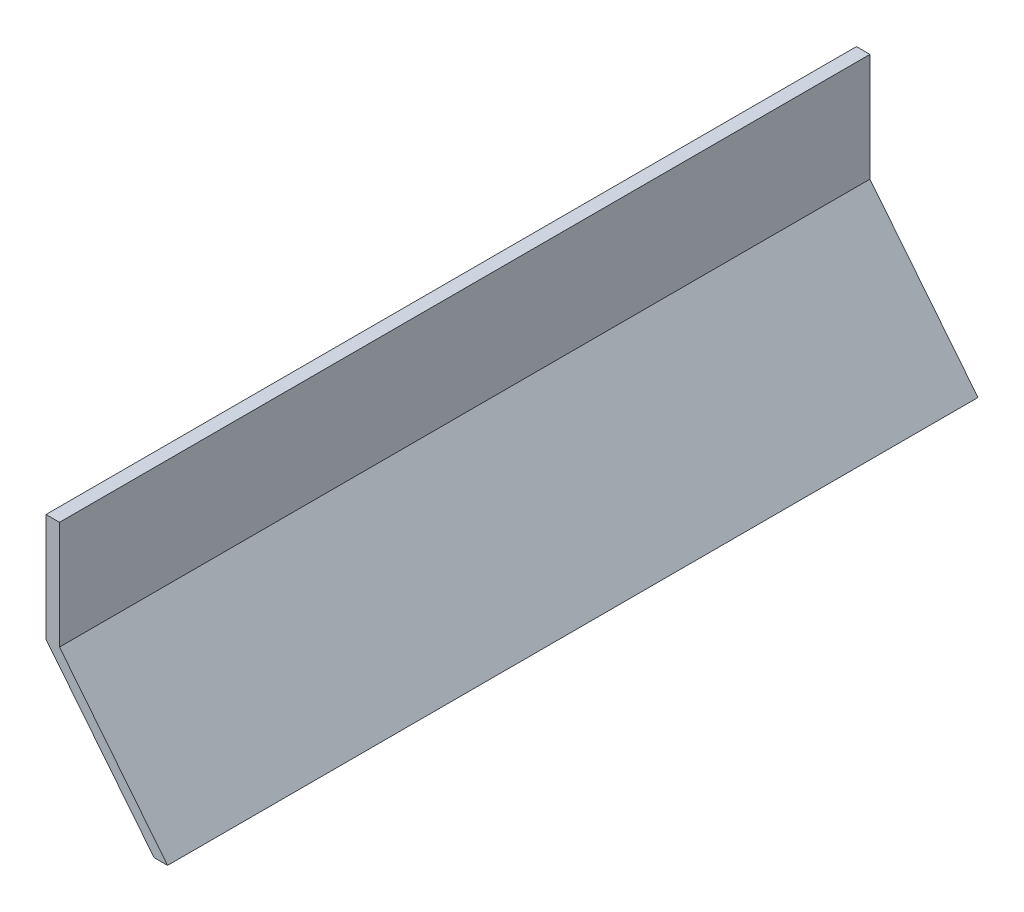
SolidWorks part; units mm, degrees
ref_plane "前基準面" through (0, 0, 0) normal (0, 0, 1) x (1, 0, 0)
ref_plane "上基準面" through (0, 0, 0) normal (0, 1, 0) x (1, 0, 0)
ref_plane "右基準面" through (0, 0, 0) normal (1, 0, 0) x (0, 0, -1)
sketch "草圖1" plane through (0, 0, 0) normal (0, 0, 1) x (1, 0, 0)
  line L0 (0, 0) -> (0.5, 0) construction
  line L2 (0, 0) -> (0, 4)
  line L3 (0, 4) -> (0.5, 4)
  line L4 (0.5, 0) -> (0.5, 4)
  line L5 (0, 0) -> (4, -5)
  line L6 (0.5, 0) -> (4.5, -5)
  line L7 (4, -5) -> (4.5, -5)
  point P5 (4.2055, -5)
  dimension "D1" = 0.5
  dimension "D2" = 4
  dimension "D3" = 5
  dimension "D4" = 4
extrude "填料-伸長1" add sketch "草圖1" along normal blind 30
